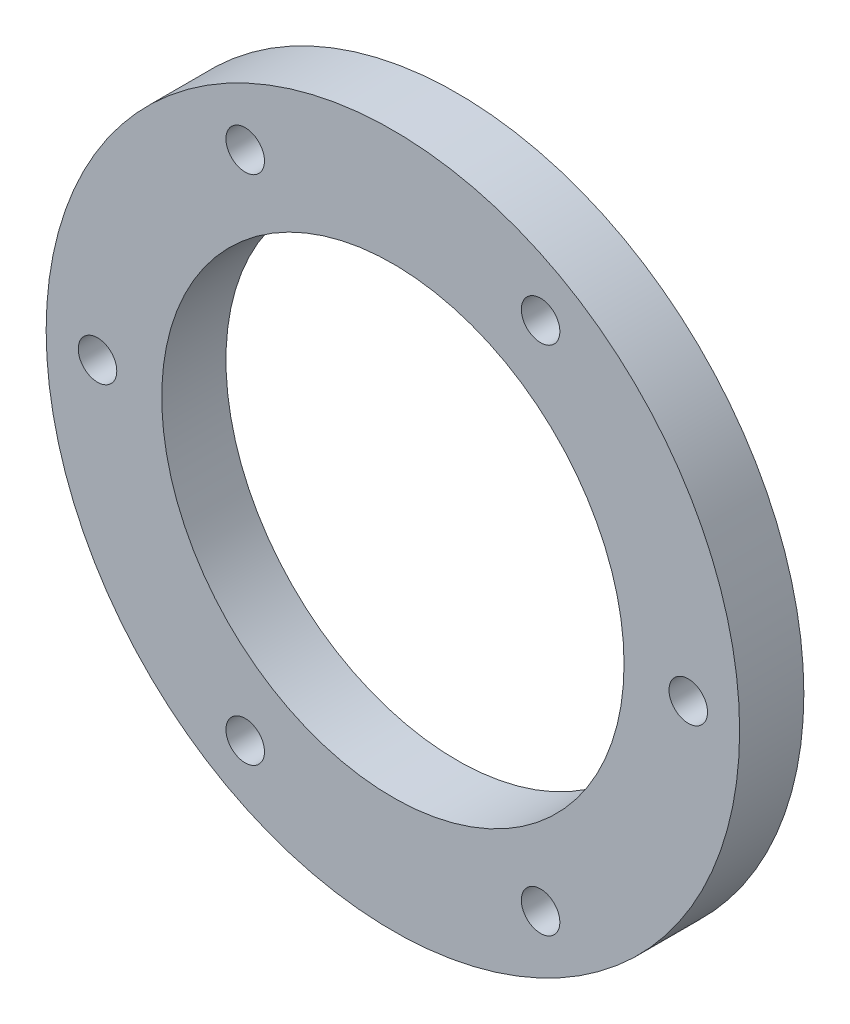
SolidWorks part; units mm, degrees
material "Acrylic (Medium-high impact)"
ref_plane "Front Plane" through (0, 0, 0) normal (0, 0, 1) x (1, 0, 0)
ref_plane "Top Plane" through (0, 0, 0) normal (0, 1, 0) x (1, 0, 0)
ref_plane "Right Plane" through (0, 0, 0) normal (1, 0, 0) x (0, 0, -1)
sketch "Sketch1" plane through (0, 0, 0) normal (0, 0, 1) x (1, 0, 0)
  line L0 (0, 34.8882) -> (0, -35.3531) construction
  line L1 (0, -35.3531) -> (0, 0) construction
  line L2 (0, 0) -> (-48.3544, 0) construction
  line L3 (-48.3544, 0) -> (47.9766, 0) construction
  line L4 (-26.5908, 46.0566) -> (27.6893, -47.9592) construction
  line L5 (27.6893, -47.9592) -> (0, 0) construction
  line L6 (0, 0) -> (21.8015, 37.7613) construction
  line L7 (0, 0) -> (-24.3439, -42.1648) construction
  circle A0 centre (0, 0) radius 27
  circle A2 centre (0, 0) radius 18
  circle A7 centre (0, 0) radius 23 construction
  circle A8 centre (-11.5, 19.9186) radius 1.5
  circle A9 centre (-23, 0) radius 1.5
  circle A10 centre (-11.5, -19.9186) radius 1.5
  circle A12 centre (11.5, -19.9186) radius 1.5
  circle A13 centre (23, 0) radius 1.5
  circle A14 centre (11.5, 19.9186) radius 1.5
  dimension "D2" = 60
  dimension "D4" = 3
  dimension "D5" = 3
  dimension "D3" = 60
extrude "Boss-Extrude1" add sketch "Sketch1" along normal blind 5
